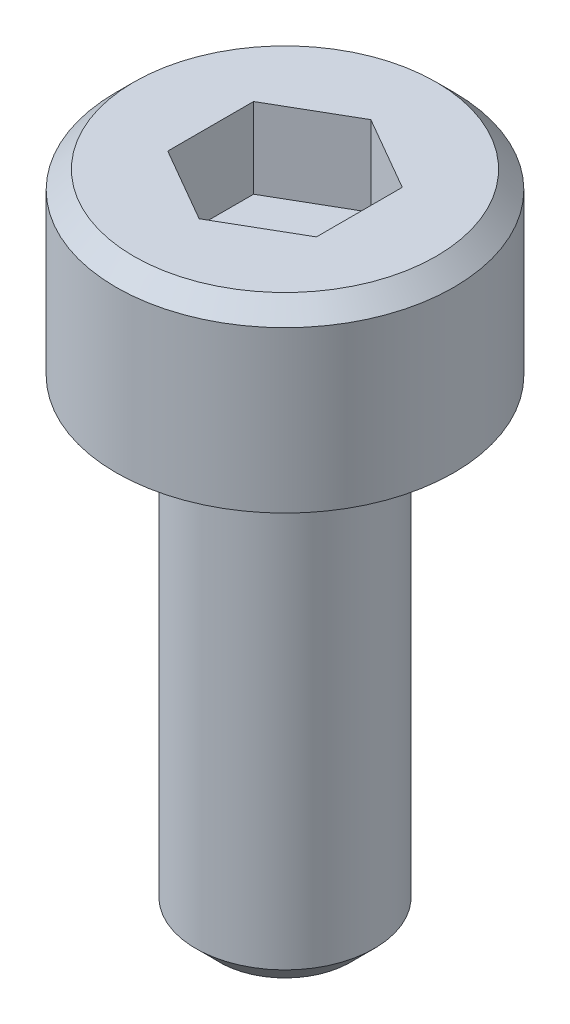
SolidWorks part; units mm, degrees
ref_plane "Front Plane" through (0, 0, 0) normal (0, 0, 1) x (1, 0, 0)
ref_plane "Top Plane" through (0, 0, 0) normal (0, 1, 0) x (1, 0, 0)
ref_plane "Right Plane" through (0, 0, 0) normal (1, 0, 0) x (0, 0, -1)
sketch "Sketch1" plane through (0, 0, 0) normal (0, 0, 1) x (1, 0, 0)
  line L0 (0, -8) -> (1.1, -8)
  line L1 (1.1, -8) -> (1.5, -7.6)
  line L2 (1.5, -7.6) -> (1.5, 0)
  line L3 (1.5, 0) -> (2.84, 0)
  line L4 (2.84, 0) -> (2.84, 2.7)
  line L5 (2.84, 2.7) -> (2.54, 3)
  line L6 (2.54, 3) -> (0, 3)
  line L7 (0, 3) -> (0, -8)
  line L8 (0, -10) -> (0, 1000) construction
revolve "Revolve1" add sketch "Sketch1" angle 360 about L8
cosmetic thread "Cosmetic Thread1" parameters "D1"=7.6, "D2"=2.4588
ref_plane "Plane1" through (0, 3, 0) normal (0, 1, 0) x (1, 0, 0)
sketch "Sketch2" plane through (0, 3, 0) normal (0, 1, 0) x (1, 0, 0)
  line L0 (1.25, -0.7217) -> (0, -1.4434)
  line L1 (0, -1.4434) -> (-1.25, -0.7217)
  line L2 (-1.25, -0.7217) -> (-1.25, 0.7217)
  line L3 (-1.25, 0.7217) -> (0, 1.4434)
  line L4 (0, 1.4434) -> (1.25, 0.7217)
  line L5 (1.25, 0.7217) -> (1.25, -0.7217)
extrude "Cut-Extrude1" cut sketch "Sketch2" against normal blind 1.35
